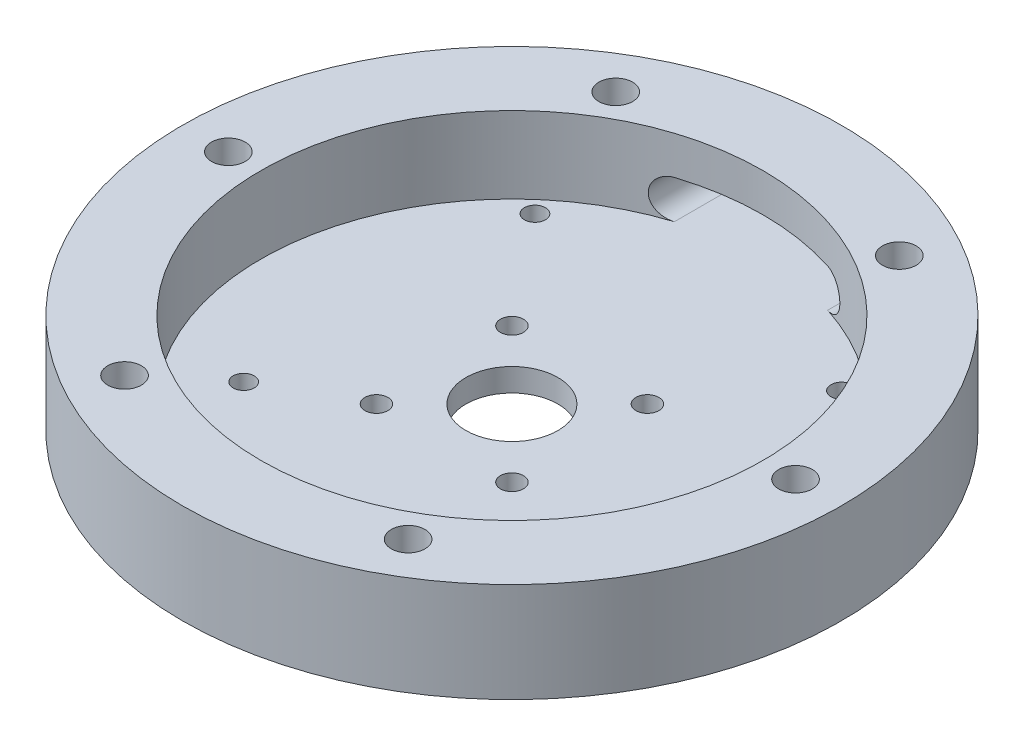
SolidWorks part; units mm, degrees
ref_plane "Front Plane" through (0, 0, 0) normal (0, 0, 1) x (1, 0, 0)
ref_plane "Top Plane" through (0, 0, 0) normal (0, 1, 0) x (1, 0, 0)
ref_plane "Right Plane" through (0, 0, 0) normal (1, 0, 0) x (0, 0, -1)
sketch "스케치1" plane through (0, 0, 0) normal (0, 1, 0) x (1, 0, 0)
  circle A0 centre (0, 0) radius 6
  circle A1 centre (0, 0) radius 43
  dimension "D1" = 12
  dimension "D6" = 86
extrude "보스-돌출1" add sketch "스케치1" along normal blind 3
sketch "스케치14" plane through (0, 3, 0) normal (0, 1, 0) x (1, 0, 0)
  circle A0 centre (0, 0) radius 32.5 construction
  circle A1 centre (0, 0) radius 43
  circle A2 centre (0, 0) radius 32.76
  dimension "D1" = 65
  dimension "D2" = 86
  dimension "D3" = 0.26
extrude "보스-돌출5" add sketch "스케치14" along normal blind 10
sketch "스케치17" plane through (0, 0, 0) normal (0, -1, 0) x (1, 0, 0)
  line L0 (0, 43) -> (0, -43) construction
  line L1 (-43, 0) -> (43, 0) construction
  circle A0 centre (0, 0) radius 43 construction
  circle A1 centre (20, 15) radius 2.35
  circle A2 centre (-20, 15) radius 2.35
  circle A3 centre (20, -23) radius 2.35
  circle A4 centre (-20, -23) radius 2.35
  point P0 (20, 15)
  point P7 (-20, 15)
  point P8 (20, -23)
  point P9 (-20, -23)
  dimension "D5" = 4.7
  dimension "D1" = 15
  dimension "D2" = 20
  dimension "D3" = 23
  dimension "D4" = 20
extrude "보스-돌출6" add sketch "스케치17" along normal blind 6.4
sketch "스케치18" plane through (0, -6.4, 0) normal (0, -1, 0) x (1, 0, 0)
  circle A0 centre (-20, 15) radius 1.375
  circle A1 centre (20, 15) radius 1.375
  circle A2 centre (20, -23) radius 1.375
  circle A3 centre (-20, -23) radius 1.375
  point P0 (-20, 15)
  point P1 (20, 15)
  point P3 (20, -23)
  point P5 (-20, -23)
  dimension "D1" = 2.75
sketch "스케치23" plane through (0, 13, 0) normal (0, 1, 0) x (1, 0, 0)
  line L0 (0, 0) -> (0, 43) construction
  line L1 (0, 0) -> (21.5, 37.2391) construction
  circle A0 centre (0, 0) radius 43 construction
  circle A2 centre (18.5, 32.0429) radius 2.2
  point P8 (18.5, 32.0429)
  dimension "D4" = 4.4
  dimension "D3" = 6
  dimension "D5" = 30
sketch "스케치26" plane through (0, 3, 0) normal (0, 1, 0) x (1, 0, 0)
  line L0 (0, 0) -> (0, 13.7193) construction
  line L1 (0, 0) -> (8.8388, 8.8388) construction
  circle A1 centre (8.8388, 8.8388) radius 1.5
  dimension "D3" = 3
  dimension "D1" = 45
  dimension "D2" = 12.5
ref_plane "Plane1" through (0, 0, -43) normal (0, 0, -1) x (-1, 0, 0)
extrude "컷-돌출5" cut sketch "스케치18" against normal through all
extrude "컷-돌출6" cut sketch "스케치23" against normal blind 6.1
sketch "Sketch2" plane through (0, 0, -43) normal (0, 0, -1) x (-1, 0, 0)
  line L0 (0, 0) -> (0, 16.2829) construction
  line L1 (-43, 0) -> (43, 0) construction
  line L2 (0, 15.15) -> (0, -2) construction
  line L4 (-10, 5.5) -> (10, 5.5) construction
  line L5 (-10, 8) -> (10, 8)
  line L6 (-10, 3) -> (10, 3)
  arc A0 (-10, 8) -> (-10, 3) centre (-10, 5.5) ccw
  arc A1 (10, 3) -> (10, 8) centre (10, 5.5) ccw
  point P0 (0, 0)
  point P13 (0, 5.5)
  dimension "D2" = 2.5
  dimension "D3" = 20
  dimension "D4" = 3
extrude "Cut-Extrude1" cut sketch "Sketch2" against normal blind 20
extrude "Cut-Extrude3" cut sketch "스케치26" against normal blind 6.1 contours A1
pattern_circular "CirPattern1" count 4 over 360 about axis through (0, 0, 0) along (0, 1, 0) of "Cut-Extrude3"
pattern_circular "CirPattern2" count 6 over 360 about axis through (0, 0, 0) along (0, 1, 0) of "컷-돌출6"
equation "\"Diameter\"= \"Inner_Diameter\" + 21"
equation "\"Inner_Diameter\"= \"Motor_Diameter\" + 2"
equation "\"Bottom_Shell_Height\"= 10"
equation "\"Screw_Placement_Diameter\"= 74"
equation "\"Stand_Height\"= 6.4"
equation "\"Motor_Diameter\"= 63"
equation "\"Motor_Base_Diameter\"= 38"
equation "\"D6@스케치1\"=\"Diameter\""
equation "\"Bottom_Gap\"= 12"
equation "\"D1@스케치14\"=\"Inner_Diameter\""
equation "\"M3-Thread-Hole\"= 4.4"
equation "\"D4@스케치23\"=\"M3-Thread-Hole\""
equation "\"M3\"= 3"
equation "\"D3@스케치26\"=\"M3\""
equation "\"D3@스케치27\"=\"M3\""
